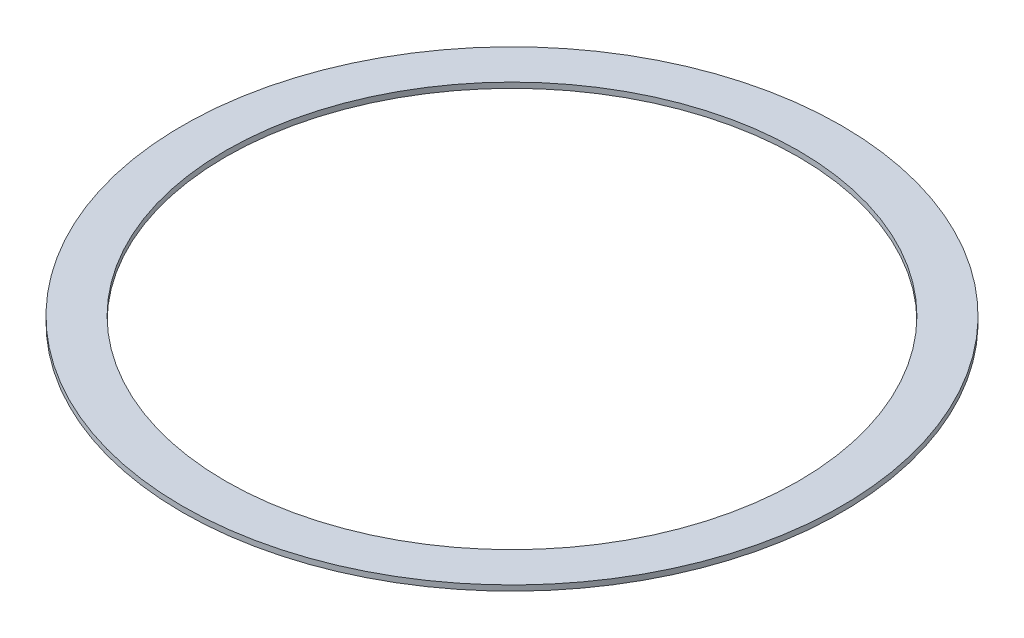
SolidWorks part; units mm, degrees
ref_plane "前视基准面" through (0, 0, 0) normal (0, 0, 1) x (1, 0, 0)
ref_plane "上视基准面" through (0, 0, 0) normal (0, 1, 0) x (1, 0, 0)
ref_plane "右视基准面" through (0, 0, 0) normal (1, 0, 0) x (0, 0, -1)
other "Configuration Table"
sketch "草图1" plane through (0, 0, 0) normal (0, 1, 0) x (1, 0, 0)
  circle A0 centre (0, 0) radius 26.5
  circle A1 centre (0, 0) radius 30.5
  dimension "D1" = 53
  dimension "D2" = 61
extrude "凸台-拉伸1" add sketch "草图1" along normal blind 0.5
